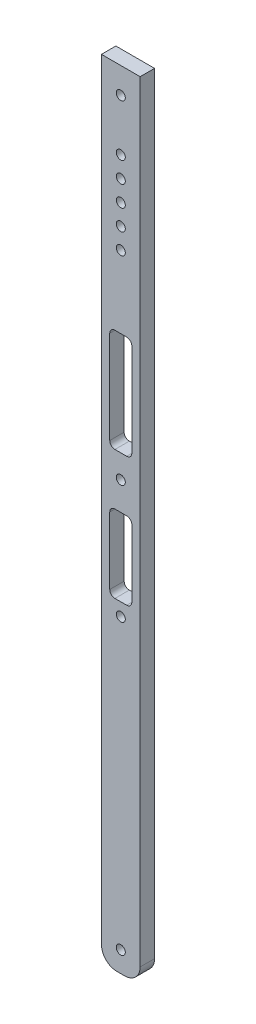
SolidWorks part; units mm, degrees
ref_plane "Front Plane" through (0, 0, 0) normal (0, 0, 1) x (1, 0, 0)
ref_plane "Top Plane" through (0, 0, 0) normal (0, 1, 0) x (1, 0, 0)
ref_plane "Right Plane" through (0, 0, 0) normal (1, 0, 0) x (0, 0, -1)
sketch "Sketch1" plane through (0, 0, 0) normal (0, 0, 1) x (1, 0, 0)
  line L1 (-5.1892, -216.5025) -> (9.8108, -216.5025)
  line L2 (-5.1892, -216.5025) -> (-5.1892, 88.2975)
  line L3 (-5.1892, 88.2975) -> (9.8108, 88.2975)
  line L4 (9.8108, -216.5025) -> (9.8108, 88.2975)
  dimension "D1" = 15
  dimension "D2" = 304.8
extrude "Boss-Extrude1" add sketch "Sketch1" along normal blind 5.588
sketch "Sketch2" plane through (0, 0, 5.588) normal (0, 0, 1) x (1, 0, 0)
  line L1 (2.3108, 88.2975) -> (2.3108, -216.5025) construction
  line L2 (9.8108, 88.2975) -> (-5.1892, 88.2975) construction
  line L3 (-5.1892, -216.5025) -> (9.8108, -216.5025) construction
  line L5 (0.0295, -1.7025) -> (4.5922, -1.7025)
  line L6 (-1.9705, -3.7025) -> (-1.9705, -39.7025)
  line L7 (0.0295, -41.7025) -> (4.5922, -41.7025)
  line L8 (6.5922, -3.7025) -> (6.5922, -39.7025)
  line L9 (0.0295, -61.7025) -> (4.5922, -61.7025)
  line L10 (-1.9705, -63.7025) -> (-1.9705, -89.7025)
  line L11 (0.0295, -91.7025) -> (4.5922, -91.7025)
  line L12 (6.5922, -63.7025) -> (6.5922, -89.7025)
  circle A0 centre (2.3108, 78.2975) radius 1.75
  circle A1 centre (2.3108, 58.2975) radius 1.75
  circle A2 centre (2.3108, 50.2975) radius 1.75
  circle A3 centre (2.3108, 42.2975) radius 1.75
  circle A4 centre (2.3108, 34.2975) radius 1.75
  circle A5 centre (2.3108, 26.2975) radius 1.75
  circle A6 centre (2.3108, -50.7628) radius 1.75
  circle A7 centre (2.3108, -96.7025) radius 1.75
  arc A8 (4.5922, -91.7025) -> (6.5922, -89.7025) centre (4.5922, -89.7025) ccw
  arc A9 (-1.9705, -89.7025) -> (0.0295, -91.7025) centre (0.0295, -89.7025) ccw
  arc A10 (4.5922, -61.7025) -> (6.5922, -63.7025) centre (4.5922, -63.7025) cw
  arc A11 (0.0295, -61.7025) -> (-1.9705, -63.7025) centre (0.0295, -63.7025) ccw
  arc A12 (6.5922, -39.7025) -> (4.5922, -41.7025) centre (4.5922, -39.7025) cw
  arc A13 (-1.9705, -39.7025) -> (0.0295, -41.7025) centre (0.0295, -39.7025) ccw
  arc A14 (6.5922, -3.7025) -> (4.5922, -1.7025) centre (4.5922, -3.7025) ccw
  arc A15 (0.0295, -1.7025) -> (-1.9705, -3.7025) centre (0.0295, -3.7025) ccw
  point P34 (6.5922, -91.7025)
  point P39 (6.5922, -61.7025)
  point P44 (6.5922, -41.7025)
  point P49 (6.5922, -1.7025)
  dimension "D1" = 3.5
  dimension "D3" = 3.5
  dimension "D14" = 2
  dimension "D2" = 10
  dimension "D4" = 8
  dimension "D5" = 8
  dimension "D6" = 8
  dimension "D7" = 8
  dimension "D8" = 20
  dimension "D9" = 40
  dimension "D10" = 30
  dimension "D11" = 90
  dimension "D12" = 150
  dimension "D13" = 5
extrude "Cut-Extrude1" cut sketch "Sketch2" against normal through all
sketch "Sketch3" plane through (0, 0, 5.588) normal (0, 0, 1) x (1, 0, 0)
  line L0 (2.3108, -216.5025) -> (2.3108, -92.1446) construction
  line L1 (-5.1892, -216.5025) -> (9.8108, -216.5025) construction
  circle A0 centre (2.3108, -208.5025) radius 1.75
  dimension "D1" = 3.5
  dimension "D2" = 8
extrude "Cut-Extrude2" cut sketch "Sketch3" against normal through all
fillet "Fillet1" radius 6 2 edges at (9.8108, -216.5025, 2.794) (-5.1892, -216.5025, 2.794)
